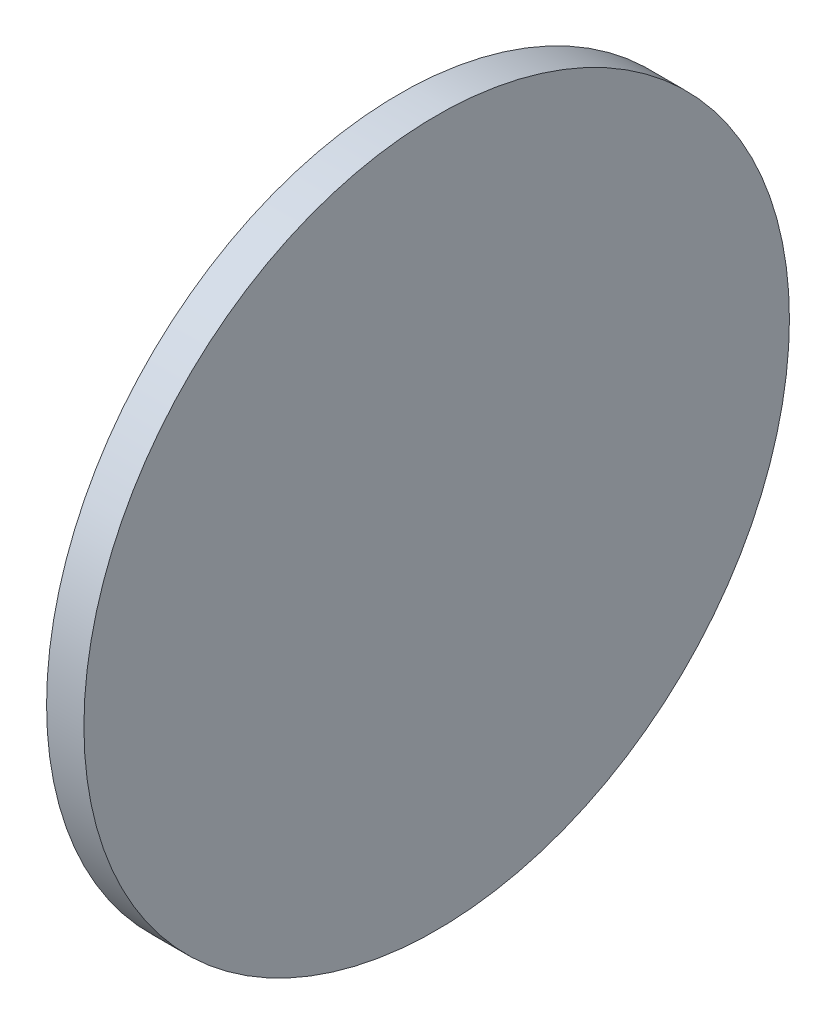
SolidWorks part; units mm, degrees
ref_plane "Front Plane" through (0, 0, 0) normal (0, 0, 1) x (1, 0, 0)
ref_plane "Top Plane" through (0, 0, 0) normal (0, 1, 0) x (1, 0, 0)
ref_plane "Right Plane" through (0, 0, 0) normal (1, 0, 0) x (0, 0, -1)
sketch "Sketch1" plane through (0, 0, 0) normal (1, 0, 0) x (0, 0, -1)
  circle A0 centre (-1.7759, 2.6639) radius 30
extrude "Extrude1" add sketch "Sketch1" along normal blind 3.175
